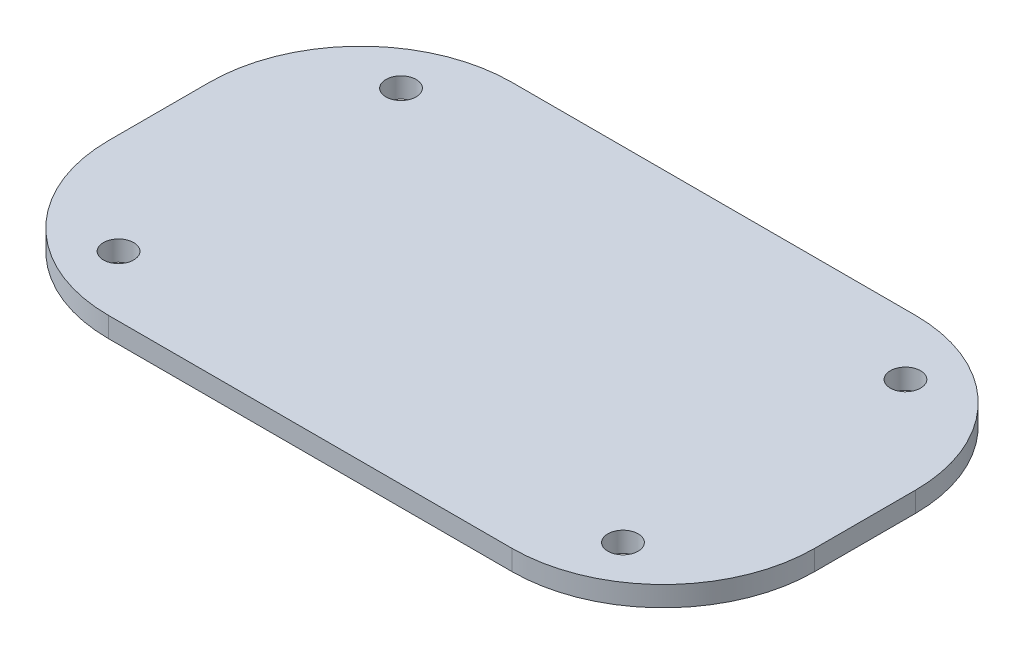
SolidWorks part; units mm, degrees
ref_plane "前视基准面" through (0, 0, 0) normal (0, 0, 1) x (1, 0, 0)
ref_plane "上视基准面" through (0, 0, 0) normal (0, 1, 0) x (1, 0, 0)
ref_plane "右视基准面" through (0, 0, 0) normal (1, 0, 0) x (0, 0, -1)
sketch "草图1" plane through (0, 0, 0) normal (0, 1, 0) x (1, 0, 0)
  line L1 (-35, -20) -> (35, -20)
  line L2 (-35, -20) -> (-35, 20)
  line L3 (-35, 20) -> (35, 20)
  line L4 (35, -20) -> (35, 20)
  line L5 (-35, -20) -> (35, 20) construction
  line L6 (-35, 20) -> (35, -20) construction
  point P0 (0, 0)
  dimension "D1" = 70
  dimension "D2" = 40
extrude "凸台-拉伸1" add sketch "草图1" along normal blind 2
fillet "圆角1" radius 15 4 edges at (-35, 1, 20) (35, 1, 20) (35, 1, -20) (-35, 1, -20)
sketch "草图2" plane through (0, 2, 0) normal (0, 1, 0) x (1, 0, 0)
  line L1 (-25, -14) -> (25, -14) construction
  line L2 (-25, -14) -> (-25, 14) construction
  line L3 (-25, 14) -> (25, 14) construction
  line L4 (25, -14) -> (25, 14) construction
  line L5 (-25, -14) -> (25, 14) construction
  line L6 (-25, 14) -> (25, -14) construction
  circle A0 centre (-25, 14) radius 1.5
  circle A1 centre (25, 14) radius 1.5
  circle A2 centre (25, -14) radius 1.5
  circle A3 centre (-25, -14) radius 1.5
  point P0 (0, 0)
  dimension "D1" = 50
  dimension "D3" = 3
  dimension "D2" = 28
extrude "切除-拉伸1" cut sketch "草图2" against normal through all
